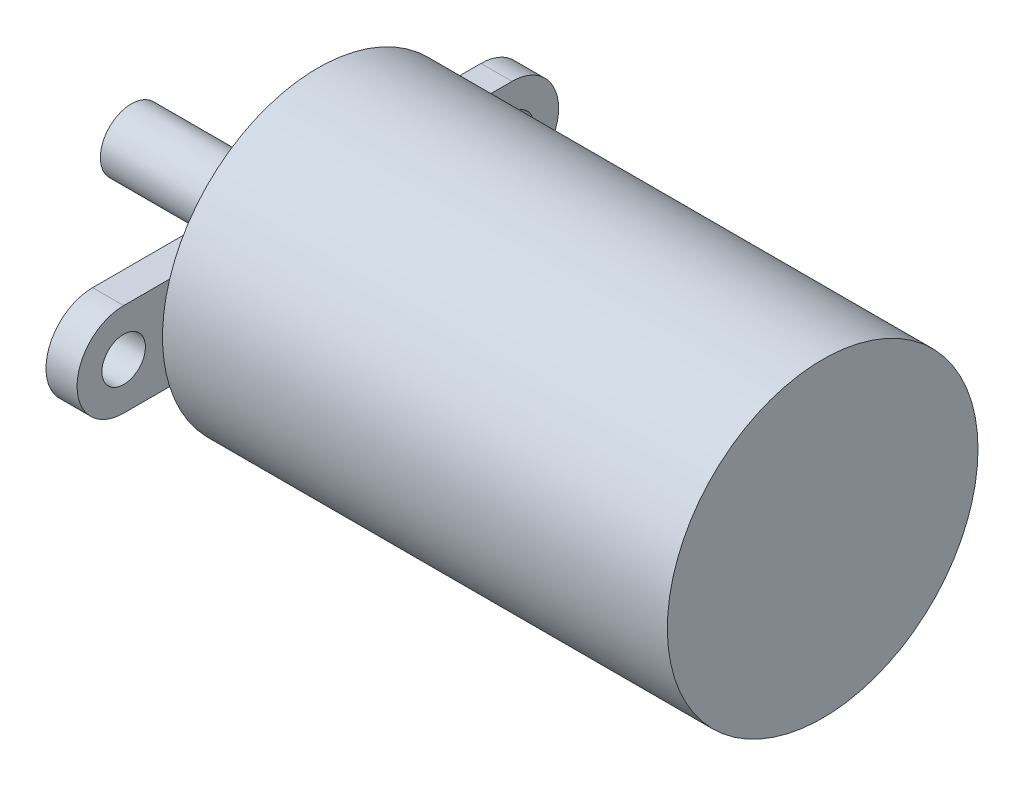
SolidWorks part; units mm, degrees
material "ABS"
ref_plane "Front" through (0, 0, 0) normal (0, 0, 1) x (1, 0, 0)
ref_plane "Top" through (0, 0, 0) normal (0, 1, 0) x (1, 0, 0)
ref_plane "Right" through (0, 0, 0) normal (1, 0, 0) x (0, 0, -1)
sketch "Sketch1" plane through (0, 0, 0) normal (1, 0, 0) x (0, 0, -1)
  circle A0 centre (0, 0) radius 10
  dimension "D1" = 20
extrude "Boss-Extrude1" add sketch "Sketch1" along normal blind 32.5
sketch "Sketch2" plane through (0, 0, 0) normal (-1, 0, 0) x (0, 0, 1)
  line L0 (-12.5, 0) -> (12.5, 0) construction
  line L1 (-12.5, 3) -> (12.5, 3)
  line L2 (-12.5, -3) -> (12.5, -3)
  arc A0 (-12.5, 3) -> (-12.5, -3) centre (-12.5, 0) ccw
  arc A1 (12.5, -3) -> (12.5, 3) centre (12.5, 0) ccw
  point P2 (0, 0)
  dimension "D1" = 3
  dimension "D2" = 25
extrude "Boss-Extrude2" add sketch "Sketch2" along normal blind 2
hole_wizard "Ø2.8 (2.8) Diameter Hole1" positions "Sketch4" profile "Sketch3" hole size "Ø2.8" standard "Ansi Metric"
sketch "Sketch4" plane through (-2, 0, 0) normal (-1, 0, 0) x (0, 0, 1)
  arc A0 (-12.5, 3) -> (-12.5, -3) centre (-12.5, 0) ccw construction
  arc A1 (12.5, -3) -> (12.5, 3) centre (12.5, 0) ccw construction
  point P0 (-12.5, -0.1403)
  point P1 (12.5, 0)
  dimension "D1" = 0
  dimension "D2" = 0
sketch "Sketch3" plane through (-2, -0.1403, -12.5) normal (0, 1, 0) x (0, 0, 1)
  line L0 (0, 0) -> (0, 70.8412)
  line L1 (0, 70.8412) -> (1.4, 70)
  line L2 (1.4, 70) -> (1.4, 0)
  line L5 (1.4, 0) -> (0, 0)
  line L10 (0, 70.8412) -> (-1.4, 70) construction
  line L11 (0, -6.35) -> (0, 107.95) construction
  dimension "Hole Dia." = 2.8
  dimension "Hole Depth" = 70
  dimension "Drill Angle" = 118
sketch "Sketch5" plane through (-2, 0, 0) normal (-1, 0, 0) x (0, 0, 1)
  circle A0 centre (0, 0) radius 4
  dimension "D1" = 8
extrude "Boss-Extrude3" add sketch "Sketch5" along normal blind 2
sketch "Sketch6" plane through (-4, 0, 0) normal (-1, 0, 0) x (0, 0, 1)
  circle A0 centre (0, 0) radius 2
  dimension "D1" = 4
extrude "Boss-Extrude4" add sketch "Sketch6" along normal blind 8
